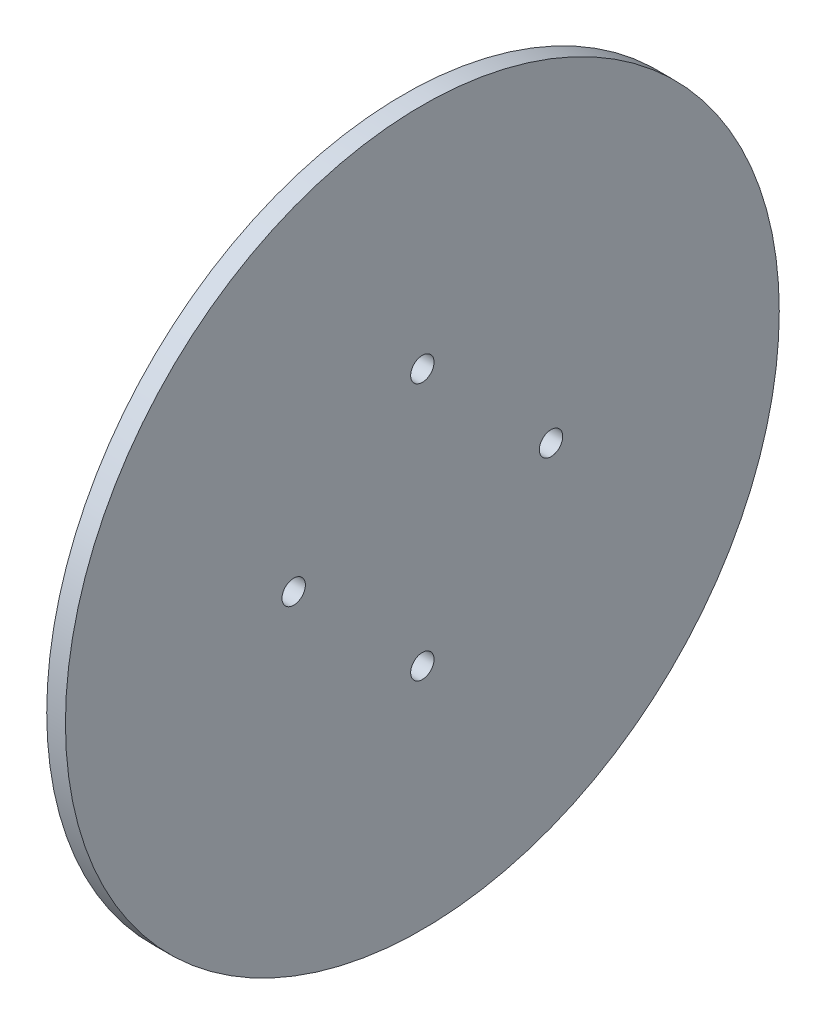
SolidWorks part; units mm, degrees
ref_plane "Front Plane" through (0, 0, 0) normal (0, 0, 1) x (1, 0, 0)
ref_plane "Top Plane" through (0, 0, 0) normal (0, 1, 0) x (1, 0, 0)
ref_plane "Right Plane" through (0, 0, 0) normal (1, 0, 0) x (0, 0, -1)
sketch "Sketch1" plane through (0, 0, 0) normal (1, 0, 0) x (0, 0, -1)
  line L0 (-76.29, 0) -> (76.29, 0) construction
  line L1 (0, 76.29) -> (0, -76.29) construction
  circle A0 centre (0, 0) radius 76.29
  circle A1 centre (0, 27.5) radius 2.5
  circle A2 centre (27.5, 0) radius 2.5
  circle A3 centre (0, -27.5) radius 2.5
  circle A4 centre (-27.5, 0) radius 2.5
  point P11 (0, 0)
  point P15 (0, 0)
  dimension "D1" = 152.58
  dimension "D2" = 5
  dimension "D3" = 55
  dimension "D4" = 4
extrude "Boss-Extrude1" add sketch "Sketch1" along normal blind 4
